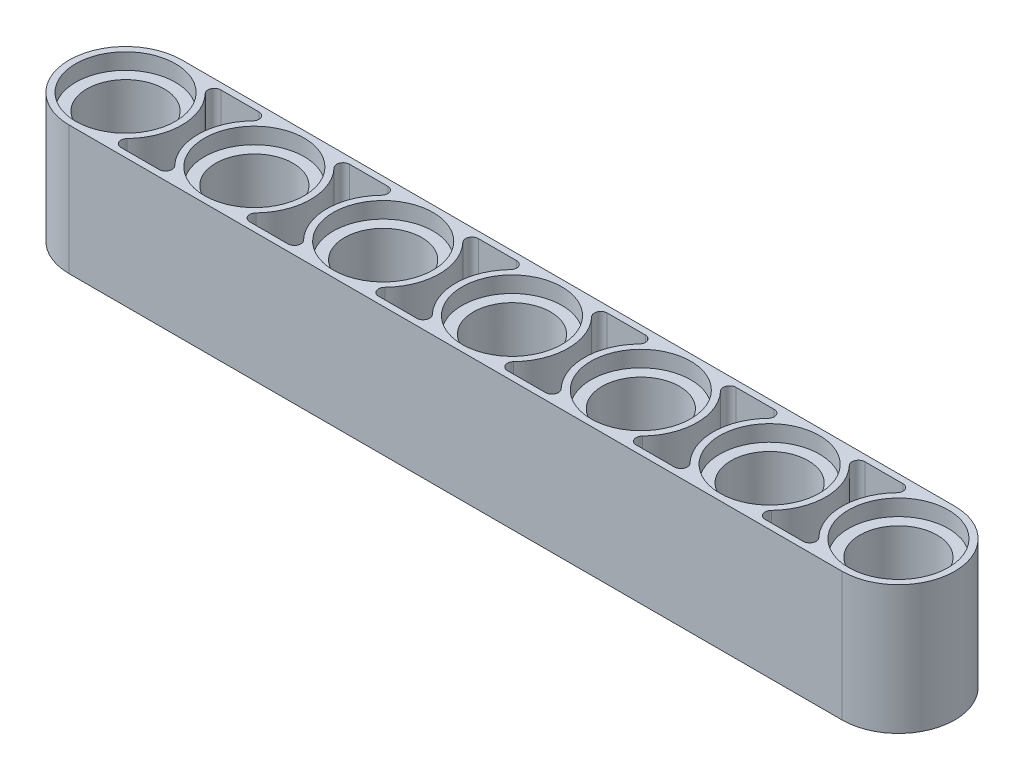
SolidWorks part; units mm, degrees
ref_plane "Front Plane" through (0, 0, 0) normal (0, 0, 1) x (1, 0, 0)
ref_plane "Top Plane" through (0, 0, 0) normal (0, 1, 0) x (1, 0, 0)
ref_plane "Right Plane" through (0, 0, 0) normal (1, 0, 0) x (0, 0, -1)
sketch "Sketch3" plane through (0, 0, 0) normal (0, 1, 0) x (1, 0, 0)
  line L0 (0, 0) -> (48, 0) construction
  line L1 (0, 3.5) -> (48, 3.5)
  line L2 (0, -3.5) -> (48, -3.5)
  arc A0 (0, 3.5) -> (0, -3.5) centre (0, 0) ccw
  arc A1 (48, -3.5) -> (48, 3.5) centre (48, 0) ccw
  point P3 (24, 0)
  point P8 (-3.5, 0)
  point P9 (51.5, 0)
  dimension "D1" = 55
  dimension "D2" = 7
extrude "Boss-Extrude1" add sketch "Sketch3" along normal blind 8
sketch "Sketch5" plane through (0, 0, 0) normal (0, -1, 0) x (-1, 0, 0)
  circle A0 centre (0, 0) radius 3.1
  dimension "D1" = 6.2
extrude "Cut-Extrude1" cut sketch "Sketch5" against normal blind 1
sketch "Sketch6" plane through (0, 1, 0) normal (0, -1, 0) x (-1, 0, 0)
  circle A0 centre (0, 0) radius 2.4
  dimension "D1" = 4.8
extrude "Cut-Extrude2" cut sketch "Sketch6" against normal through all both and the other way through all
sketch "Sketch8" plane through (0, 8, 0) normal (0, 1, 0) x (1, 0, 0)
  circle A0 centre (0, 0) radius 3.1
  dimension "D1" = 6.2
extrude "Cut-Extrude3" cut sketch "Sketch8" against normal blind 1
pattern_linear "LPattern3" count 7 spacing 8 along (1, 0, 0) of "Cut-Extrude3", "Cut-Extrude2", "Cut-Extrude1"
sketch "Sketch9" plane through (0, 8, 0) normal (0, 1, 0) x (1, 0, 0)
  line L0 (2.8142, 3.1) -> (5.1858, 3.1)
  line L1 (2.8142, -3.1) -> (5.1858, -3.1)
  arc A0 (2.5256, -2.4231) -> (2.5256, 2.4231) centre (0, 0) ccw
  arc A1 (5.4744, 2.4231) -> (5.4744, -2.4231) centre (8, 0) ccw
  arc A6 (2.5256, -2.4231) -> (2.8142, -3.1) centre (2.8142, -2.7) ccw
  arc A7 (5.1858, -3.1) -> (5.4744, -2.4231) centre (5.1858, -2.7) ccw
  arc A8 (5.4744, 2.4231) -> (5.1858, 3.1) centre (5.1858, 2.7) ccw
  arc A9 (2.8142, 3.1) -> (2.5256, 2.4231) centre (2.8142, 2.7) ccw
  dimension "D1" = 7
  dimension "D2" = 7
  dimension "D3" = 0.4
extrude "Cut-Extrude4" cut sketch "Sketch9" against normal through all and the other way through all
pattern_linear "LPattern4" count 6 spacing 8 along (1, 0, 0) of "Cut-Extrude4"
